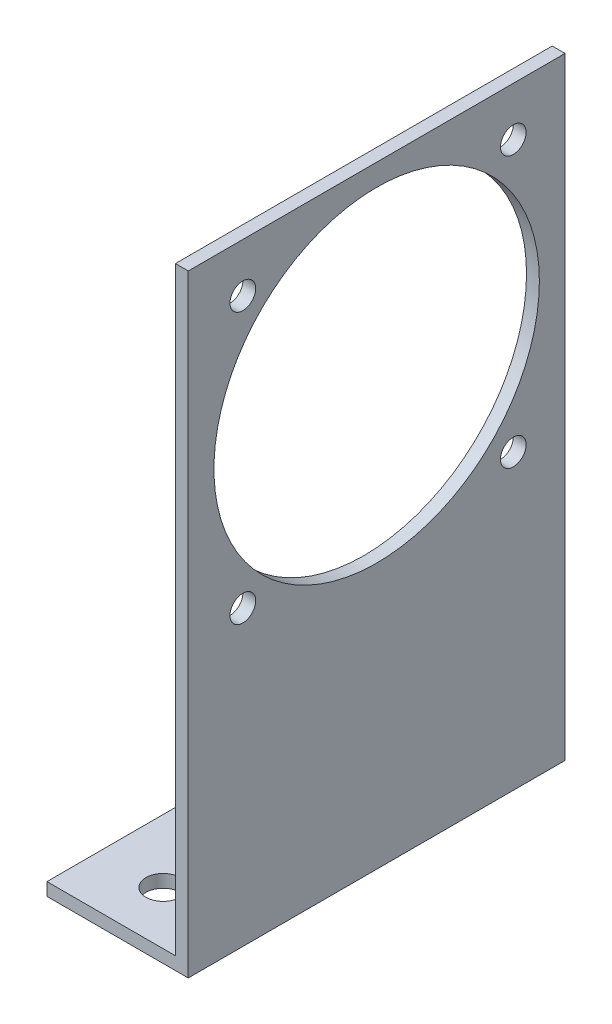
SolidWorks part; units mm, degrees
ref_plane "Front Plane" through (0, 0, 0) normal (0, 0, 1) x (1, 0, 0)
ref_plane "Top Plane" through (0, 0, 0) normal (0, 1, 0) x (1, 0, 0)
ref_plane "Right Plane" through (0, 0, 0) normal (1, 0, 0) x (0, 0, -1)
sketch "Sketch1" plane through (0, 0, 0) normal (0, 0, 1) x (1, 0, 0)
  line L0 (0, 0) -> (15, 0)
  line L1 (15, 0) -> (15, 70)
extrude "Extrude-Thin1" add sketch "Sketch1" along normal blind 44 thin
sketch "Sketch2" plane through (16.5, 0, 0) normal (1, 0, 0) x (0, 0, -1)
  circle A0 centre (-22, 48.4593) radius 19
extrude "Cut-Extrude1" cut sketch "Sketch2" against normal through all
sketch "Sketch3" plane through (0, 0, 0) normal (0, 1, 0) x (1, 0, 0)
  circle A0 centre (7.3701, -6.1914) radius 2
  circle A1 centre (7.3701, -37.8086) radius 2
extrude "Cut-Extrude2" cut sketch "Sketch3" against normal through all
sketch "Sketch4" plane through (16.5, 0, 0) normal (1, 0, 0) x (0, 0, -1)
  circle A0 centre (-37.6274, 64.3047) radius 1.5
  circle A1 centre (-6.044, 64.3047) radius 1.5
  circle A2 centre (-37.6274, 32.7192) radius 1.5
  circle A3 centre (-6.044, 32.7192) radius 1.5
extrude "Cut-Extrude3" cut sketch "Sketch4" against normal through all
